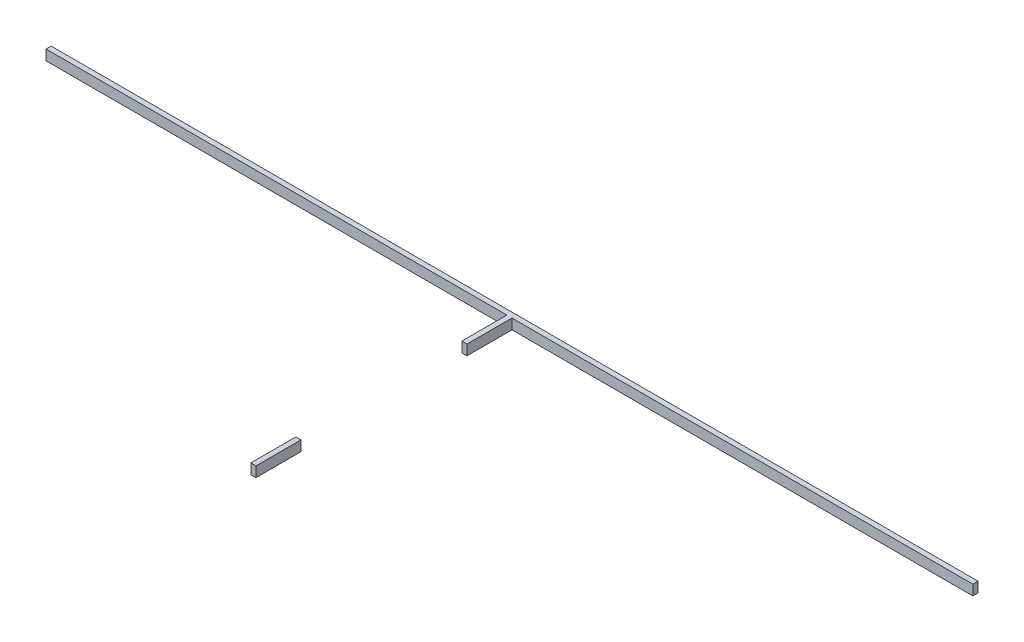
SolidWorks part; units mm, degrees
ref_plane "前视基准面" through (0, 0, 0) normal (0, 0, 1) x (1, 0, 0)
ref_plane "上视基准面" through (0, 0, 0) normal (0, 1, 0) x (1, 0, 0)
ref_plane "右视基准面" through (0, 0, 0) normal (1, 0, 0) x (0, 0, -1)
other "Configuration Table"
sketch "草图1" plane through (0, 0, 0) normal (0, 1, 0) x (1, 0, 0)
  line L0 (-4525, 0) -> (4525, 0)
  line L1 (4525, 0) -> (4525, -50)
  line L2 (4525, -50) -> (25, -50)
  line L3 (25, -50) -> (25, -490)
  line L4 (25, -490) -> (-25, -490)
  line L5 (-25, -490) -> (-25, -50)
  line L6 (-25, -50) -> (-4525, -50)
  line L7 (-4525, -50) -> (-4525, 0)
  line L9 (-25, -2110) -> (25, -2110)
  line L10 (-25, -2110) -> (-25, -2550)
  line L11 (-25, -2550) -> (25, -2550)
  line L12 (25, -2110) -> (25, -2550)
  dimension "D1" = 9050
  dimension "D2" = 50
  dimension "D3" = 50
  dimension "D4" = 25
  dimension "D5" = 440
  dimension "D6" = 440
  dimension "D7" = 1620
extrude "凸台-拉伸1" add sketch "草图1" along normal blind 100
